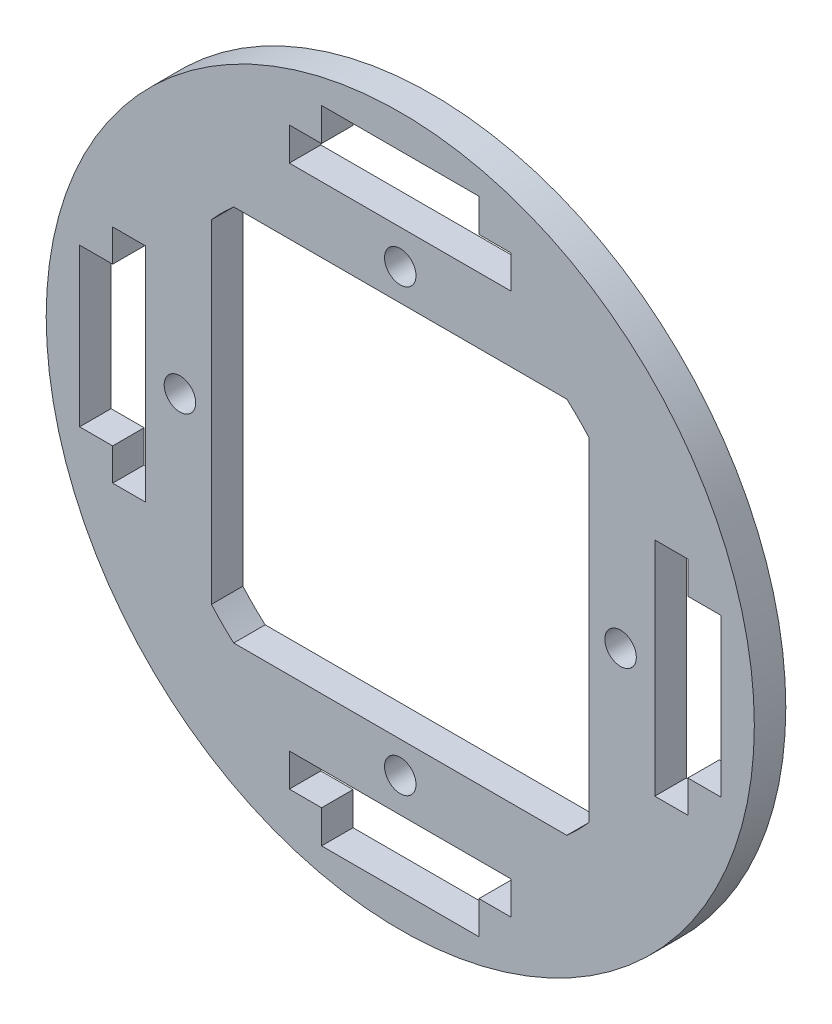
SolidWorks part; units mm, degrees
ref_plane "前视基准面" through (0, 0, 0) normal (0, 0, 1) x (1, 0, 0)
ref_plane "上视基准面" through (0, 0, 0) normal (0, 1, 0) x (1, 0, 0)
ref_plane "右视基准面" through (0, 0, 0) normal (1, 0, 0) x (0, 0, -1)
sketch "草图1" plane through (0, 0, 0) normal (0, 0, 1) x (1, 0, 0)
  line L0 (10.583, -12) -> (-10.583, -12)
  line L1 (12, 10.583) -> (12, -10.583)
  line L2 (-12, 10.583) -> (-12, -10.583)
  line L3 (-10.583, 12) -> (10.583, 12)
  line L4 (-5, 18.275) -> (-5, 20.375)
  line L5 (-18.275, 7.05) -> (-16.175, 7.05)
  line L6 (-16.175, 7.05) -> (-16.175, -7.05)
  line L7 (-16.175, -7.05) -> (-18.275, -7.05)
  line L8 (-7.05, -18.275) -> (-7.05, -16.175)
  line L9 (-7.05, -16.175) -> (7.05, -16.175)
  line L10 (7.05, -16.175) -> (7.05, -18.275)
  line L11 (18.275, -7.05) -> (16.175, -7.05)
  line L12 (16.175, -7.05) -> (16.175, 7.05)
  line L13 (16.175, 7.05) -> (18.275, 7.05)
  line L14 (5, 20.375) -> (5, 18.275)
  line L15 (7.05, 16.175) -> (-7.05, 16.175)
  line L16 (-12, 0) -> (12, 0) construction
  line L17 (0, 12) -> (0, -12) construction
  line L18 (-5, 18.275) -> (-7.05, 18.275)
  line L19 (-7.05, 18.275) -> (-7.05, 16.175)
  line L20 (5, 18.275) -> (7.05, 18.275)
  line L21 (7.05, 18.275) -> (7.05, 16.175)
  line L22 (-5, 20.375) -> (5, 20.375)
  line L23 (-18.275, 7.05) -> (-18.275, 5)
  line L24 (-18.275, 5) -> (-20.375, 5)
  line L25 (-20.375, 5) -> (-20.375, -5)
  line L26 (-20.375, -5) -> (-18.275, -5)
  line L27 (-18.275, -5) -> (-18.275, -7.05)
  line L28 (18.275, 7.05) -> (18.275, 5)
  line L29 (18.275, 5) -> (20.375, 5)
  line L30 (20.375, 5) -> (20.375, -5)
  line L31 (20.375, -5) -> (18.275, -5)
  line L32 (18.275, -5) -> (18.275, -7.05)
  line L33 (-5, -20.375) -> (-5, -18.275)
  line L34 (-7.05, -18.275) -> (-5, -18.275)
  line L35 (-5, -20.375) -> (5, -20.375)
  line L36 (5, -20.375) -> (5, -18.275)
  line L37 (7.05, -18.275) -> (5, -18.275)
  arc A0 (-12, -10.583) -> (-10.583, -12) centre (0, 0) ccw
  arc A1 (10.583, -12) -> (12, -10.583) centre (0, 0) ccw
  arc A2 (12, 10.583) -> (10.583, 12) centre (0, 0) ccw
  arc A3 (-10.583, 12) -> (-12, 10.583) centre (0, 0) ccw
  circle A4 centre (0, 0) radius 22.5
  point P36 (19.325, 5)
  dimension "D2" = 16
  dimension "D7" = 14.1
  dimension "D12" = 45
  dimension "D3" = 24
  dimension "D4" = 24
  dimension "D5" = 32.35
  dimension "D6" = 32.35
  dimension "D8" = 10
  dimension "D9" = 14.1
  dimension "D10" = 2.1
  dimension "D11" = 2.1
  dimension "D13" = 2.1
  dimension "D14" = 10
  dimension "D15" = 2.1
  dimension "D16" = 2.1
  dimension "D17" = 2.1
  dimension "D18" = 2.1
  dimension "D19" = 10
  dimension "D20" = 2.1
extrude "凸台-拉伸1" add sketch "草图1" along normal blind 2
hole_wizard "大小mm 暗销孔1" positions "草图7" profile "草图8" hole size "Ø2.0" standard "GB"
sketch "草图7" plane through (0, 0, 2) normal (0, 0, 1) x (1, 0, 0)
  point P0 (0, 14)
  point P2 (-14, 0)
  point P4 (0, -14)
  point P6 (14, 0)
  dimension "D1" = 28
  dimension "D2" = 28
  dimension "D3" = 14
  dimension "D4" = 14
sketch "草图8" plane through (0, 14, 2) normal (1, 0, 0) x (0, -1, 0)
  line L0 (0, 0) -> (0, 5.8009)
  line L1 (0, 5.8009) -> (1, 5.2)
  line L2 (1, 5.2) -> (1, 0)
  line L5 (1, 0) -> (0, 0)
  line L10 (0, 5.8009) -> (-1, 5.2) construction
  line L11 (0, -6.35) -> (0, 107.95) construction
  dimension "孔直径" = 2
  dimension "孔深度" = 5.2
  dimension "导头角度" = 118
